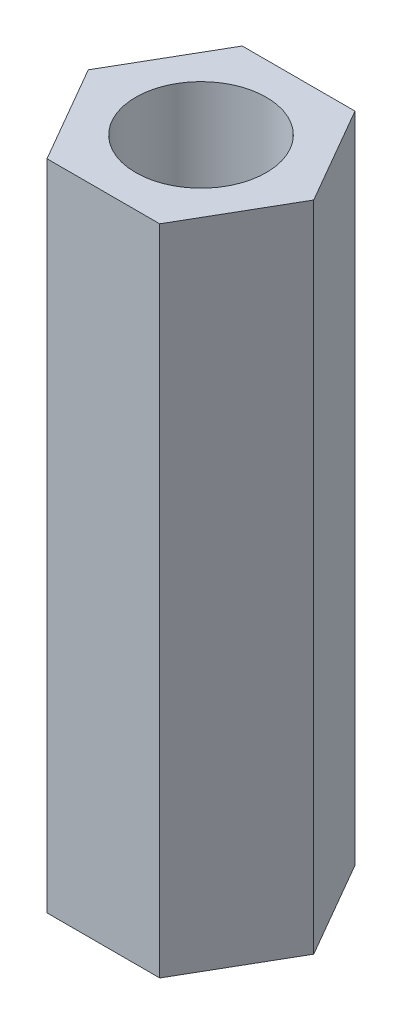
SolidWorks part; units mm, degrees
material "Nylon 6/10"
ref_plane "Front Plane" through (0, 0, 0) normal (0, 0, 1) x (1, 0, 0)
ref_plane "Top Plane" through (0, 0, 0) normal (0, 1, 0) x (1, 0, 0)
ref_plane "Right Plane" through (0, 0, 0) normal (1, 0, 0) x (0, 0, -1)
sketch "Sketch1" plane through (0, 0, 0) normal (0, 1, 0) x (1, 0, 0)
  line L1 (-1.2946, 2.2422) -> (-2.5891, 0)
  line L2 (-2.5891, 0) -> (-1.2946, -2.2422)
  line L3 (-1.2946, -2.2422) -> (1.2946, -2.2422)
  line L4 (1.2946, -2.2422) -> (2.5891, 0)
  line L5 (2.5891, 0) -> (1.2946, 2.2422)
  line L6 (1.2946, 2.2422) -> (-1.2946, 2.2422)
  circle A0 centre (0, 0) radius 1.5
  circle A1 centre (0, 0) radius 2.25 construction
  circle A2 centre (0, 0) radius 2.2422 construction
  dimension "D1" = 3
  dimension "D2" = 4.5
  dimension "D3" = 2.5891
extrude "Boss-Extrude1" add sketch "Sketch1" along normal blind 15
